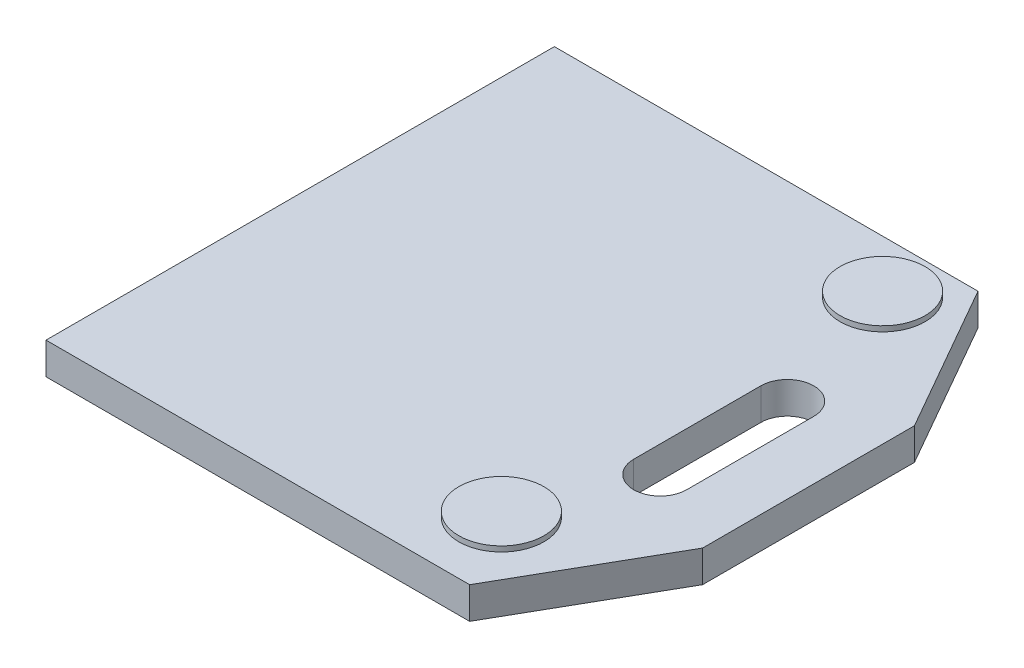
SolidWorks part; units mm, degrees
material "Pine"
ref_plane "Front Plane" through (0, 0, 0) normal (0, 0, 1) x (1, 0, 0)
ref_plane "Top Plane" through (0, 0, 0) normal (0, 1, 0) x (1, 0, 0)
ref_plane "Right Plane" through (0, 0, 0) normal (1, 0, 0) x (0, 0, -1)
sketch "Sketch3" plane through (0, 0, 0) normal (0, 1, 0) x (1, 0, 0)
  line L1 (0, 0) -> (254, 0)
  line L2 (0, 0) -> (0, -304.8)
  line L3 (0, -304.8) -> (254, -304.8)
  line L6 (254, 0) -> (304.8, -88.9)
  line L7 (304.8, -88.9) -> (304.8, -215.9)
  line L8 (304.8, -215.9) -> (254, -304.8)
  point P5 (0, 0)
  dimension "D1" = 304.8
  dimension "D2" = 254
  dimension "D5" = 127
extrude "Boss-Extrude1" add sketch "Sketch3" along normal blind 19.05
sketch "Sketch4" plane through (0, 19.05, 0) normal (0, 1, 0) x (1, 0, 0)
  circle A0 centre (228.5144, -31.7258) radius 25.4889
  circle A1 centre (228.5144, -260.29) radius 25.511
extrude "Boss-Extrude2" add sketch "Sketch4" along normal blind 3.175
sketch "Sketch5" plane through (0, 19.05, 0) normal (0, 1, 0) x (1, 0, 0)
  line L2 (253.889, -114.2314) -> (253.889, -190.4314) construction
  line L3 (269.764, -114.2314) -> (269.764, -190.4314)
  line L4 (238.014, -114.2314) -> (238.014, -190.4314)
  arc A0 (269.764, -114.2314) -> (238.014, -114.2314) centre (253.889, -114.2314) ccw
  arc A1 (238.014, -190.4314) -> (269.764, -190.4314) centre (253.889, -190.4314) ccw
  point P2 (253.889, -152.3314)
extrude "Cut-Extrude1" cut sketch "Sketch5" against normal blind 19.05
